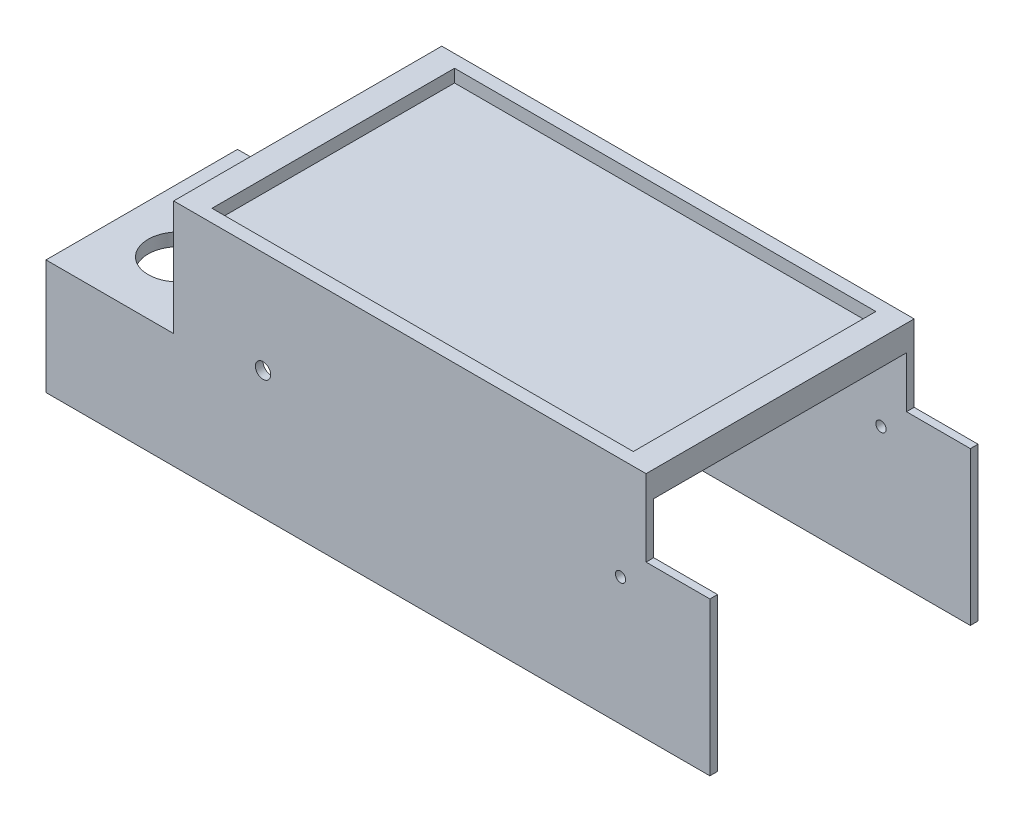
SolidWorks part; units mm, degrees
material "6061 合金"
ref_plane "前视基准面" through (0, 0, 0) normal (0, 0, 1) x (1, 0, 0)
ref_plane "上视基准面" through (0, 0, 0) normal (0, 1, 0) x (1, 0, 0)
ref_plane "右视基准面" through (0, 0, 0) normal (1, 0, 0) x (0, 0, -1)
other "Configuration Table"
sketch "草图2" plane through (0, 0, 0) normal (0, 1, 0) x (1, 0, 0)
  line L1 (-105, 52.5) -> (105, 52.5)
  line L2 (-105, 52.5) -> (-105, -52.5)
  line L3 (-105, -52.5) -> (105, -52.5)
  line L4 (105, 52.5) -> (105, -52.5)
  line L5 (-105, 52.5) -> (105, -52.5) construction
  line L6 (-105, -52.5) -> (105, 52.5) construction
  point P0 (0, 0)
  dimension "D1" = 210
  dimension "D2" = 105
extrude "凸台-拉伸1" add sketch "草图2" along normal blind 90
sketch "草图4" plane through (0, 90, 0) normal (0, 1, 0) x (1, 0, 0)
  line L0 (105, 52.5) -> (-105, 52.5) construction
  line L1 (-95, 47.5) -> (70, 47.5)
  line L2 (-95, 47.5) -> (-95, -47.5)
  line L3 (-95, -47.5) -> (70, -47.5)
  line L4 (70, 47.5) -> (70, -47.5)
  line L5 (-105, -52.5) -> (105, -52.5) construction
  line L6 (-105, 52.5) -> (-105, -52.5) construction
  dimension "D1" = 5
  dimension "D2" = 5
  dimension "D3" = 10
  dimension "D4" = 165
extrude "切除-拉伸1" cut sketch "草图4" against normal blind 5
sketch "草图5" plane through (105, 0, 0) normal (1, 0, 0) x (0, 0, -1)
  line L0 (-52.5, 0) -> (52.5, 0) construction
  line L1 (-49.5, 0) -> (49.5, 0)
  line L2 (-49.5, 0) -> (-49.5, 80)
  line L3 (-49.5, 80) -> (49.5, 80)
  line L4 (49.5, 0) -> (49.5, 80)
  line L5 (-52.5, 90) -> (-52.5, 0) construction
  line L6 (52.5, 90) -> (52.5, 0) construction
  line L7 (-52.5, 90) -> (52.5, 90) construction
  dimension "D1" = 3
  dimension "D2" = 3
  dimension "D3" = 10
extrude "切除-拉伸2" cut sketch "草图5" against normal blind 200
sketch "草图6" plane through (-105, 0, 0) normal (-1, 0, 0) x (0, 0, 1)
  line L2 (52.5, 0) -> (-22.5, 0)
  line L3 (52.5, 0) -> (52.5, 45)
  line L4 (52.5, 45) -> (-22.5, 45)
  line L5 (-22.5, 0) -> (-22.5, 45)
  dimension "D1" = 45
  dimension "D2" = 75
extrude "凸台-拉伸2" add sketch "草图6" along normal blind 50
sketch "草图7" plane through (-155, 0, 0) normal (-1, 0, 0) x (0, 0, 1)
  line L0 (-22.5, 0) -> (52.5, 0) construction
  line L1 (-19.5, 40) -> (49.5, 40)
  line L2 (-19.5, 40) -> (-19.5, 0)
  line L3 (-19.5, 0) -> (49.5, 0)
  line L4 (49.5, 40) -> (49.5, 0)
  line L5 (-22.5, 45) -> (-22.5, 0) construction
  line L6 (52.5, 0) -> (52.5, 45) construction
  line L7 (52.5, 45) -> (-22.5, 45) construction
  dimension "D1" = 3
  dimension "D2" = 3
  dimension "D3" = 5
extrude "切除-拉伸3" cut sketch "草图7" against normal through all
sketch "草图8" plane through (0, 45, 0) normal (0, 1, 0) x (1, 0, 0)
  line L0 (-155, -52.5) -> (-155, 22.5) construction
  line L1 (-155, -52.5) -> (-105, -52.5) construction
  circle A0 centre (-130, -25.5) radius 12
  dimension "D3" = 24
  dimension "D1" = 25
  dimension "D2" = 27
extrude "切除-拉伸4" cut sketch "草图8" against normal through all
sketch "草图9" plane through (0, 0, 52.5) normal (0, 0, 1) x (1, 0, 0)
  line L0 (-105, 90) -> (-105, 45) construction
  line L1 (-155, 0) -> (105, 0) construction
  line L3 (-155, 0) -> (-155, 45) construction
  circle A0 centre (-70, 50) radius 3
  circle A1 centre (70, 50) radius 2
  dimension "D3" = 6
  dimension "D4" = 4
  dimension "D5" = 225
  dimension "D1" = 35
  dimension "D2" = 50
extrude "切除-拉伸5" cut sketch "草图9" against normal through all
sketch "草图11" plane through (0, 90, 0) normal (0, 1, 0) x (1, 0, 0)
  line L0 (-105, -52.5) -> (105, -52.5) construction
  line L1 (105, 52.5) -> (80, 52.5)
  line L2 (105, 52.5) -> (105, -52.5)
  line L3 (105, -52.5) -> (80, -52.5)
  line L4 (80, 52.5) -> (80, -52.5)
  dimension "D1" = 25
extrude "切除-拉伸6" cut sketch "草图11" against normal blind 30
